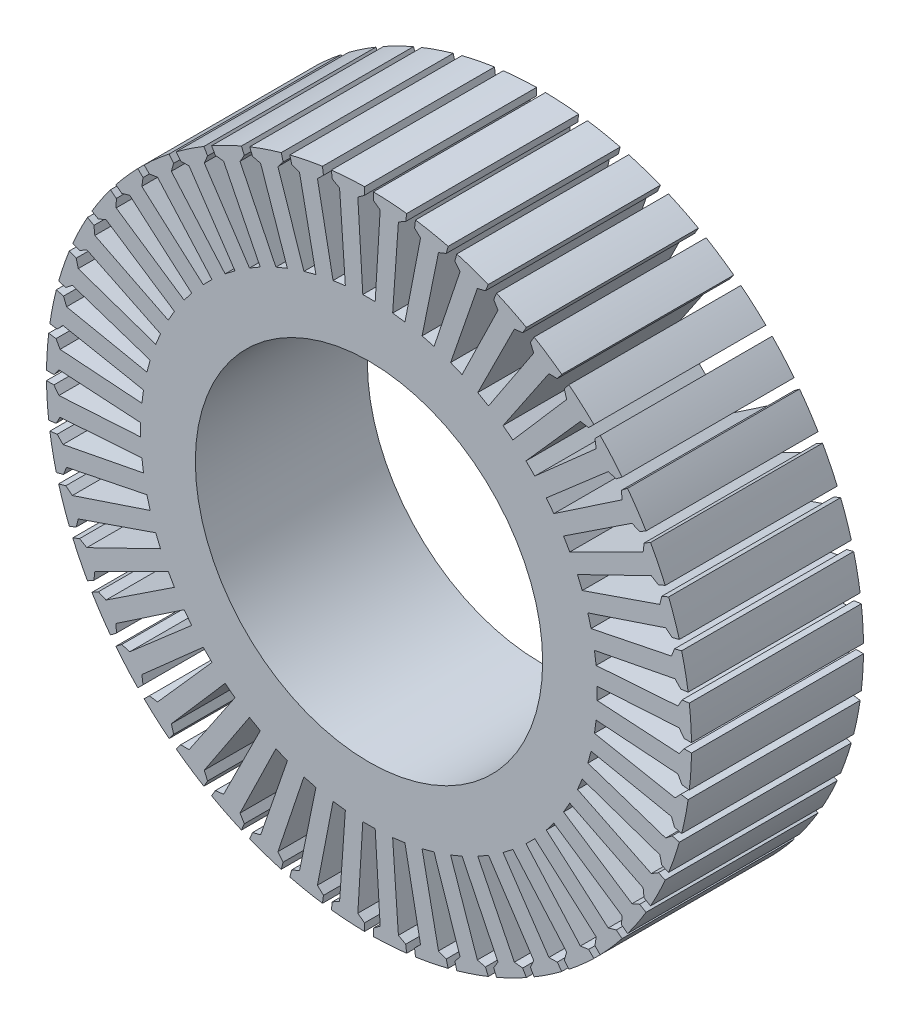
SolidWorks part; units mm, degrees
ref_plane "Спереди" through (0, 0, 0) normal (0, 0, 1) x (1, 0, 0)
ref_plane "Сверху" through (0, 0, 0) normal (0, 1, 0) x (1, 0, 0)
ref_plane "Справа" through (0, 0, 0) normal (1, 0, 0) x (0, 0, -1)
sketch "Эскиз1" plane through (0, 0, 0) normal (0, 0, 1) x (1, 0, 0)
  circle A0 centre (0, 0) radius 75
  circle A1 centre (0, 0) radius 40.3846
extrude "Stator_stack" add sketch "Эскиз1" along normal blind 40 from offset 20
sketch "Эскиз2" plane through (0, 0, 0) normal (0, 0, 1) x (1, 0, 0)
  line L0 (75.9929, -1.0385) -> (73.2692, -1.0385)
  line L1 (73.2692, -1.0385) -> (72.1154, -2.5962)
  line L2 (72.1154, -2.5962) -> (53.0769, -1.4423)
  line L3 (53.0769, -1.4423) -> (53.0769, 1.4423)
  line L4 (53.0769, 1.4423) -> (72.1154, 2.5962)
  line L5 (72.1154, 2.5962) -> (73.2692, 1.0385)
  line L6 (73.2692, 1.0385) -> (75.9929, 1.0385)
  line L7 (75.9929, 1.0385) -> (75.9929, -1.0385)
  line L8 (75.4783, 8.8895) -> (72.7779, 8.534)
  line L9 (72.7779, 8.534) -> (71.8373, 6.839)
  line L10 (71.8373, 6.839) -> (52.8111, 5.498)
  line L11 (52.8111, 5.498) -> (52.4346, 8.3579)
  line L12 (52.4346, 8.3579) -> (71.1596, 11.9869)
  line L13 (71.1596, 11.9869) -> (72.5069, 10.5931)
  line L14 (72.5069, 10.5931) -> (75.2072, 10.9486)
  line L15 (75.2072, 10.9486) -> (75.4783, 8.8895)
  line L16 (73.6723, 18.6653) -> (71.0414, 17.9604)
  line L17 (71.0414, 17.9604) -> (70.33, 16.1571)
  line L18 (70.33, 16.1571) -> (51.6417, 12.3442)
  line L19 (51.6417, 12.3442) -> (50.8951, 15.1305)
  line L20 (50.8951, 15.1305) -> (68.9862, 21.1725)
  line L21 (68.9862, 21.1725) -> (70.5039, 19.9665)
  line L22 (70.5039, 19.9665) -> (73.1347, 20.6715)
  line L23 (73.1347, 20.6715) -> (73.6723, 18.6653)
  line L24 (70.6057, 28.1218) -> (68.0893, 27.0795)
  line L25 (68.0893, 27.0795) -> (67.6194, 25.1988)
  line L26 (67.6194, 25.1988) -> (49.5886, 18.9791)
  line L27 (49.5886, 18.9791) -> (48.4847, 21.6442)
  line L28 (48.4847, 21.6442) -> (65.6324, 29.9959)
  line L29 (65.6324, 29.9959) -> (67.2945, 28.9983)
  line L30 (67.2945, 28.9983) -> (69.8109, 30.0406)
  line L31 (69.8109, 30.0406) -> (70.6057, 28.1218)
  line L32 (66.331, 37.0971) -> (63.9722, 35.7353)
  line L33 (63.9722, 35.7353) -> (63.7518, 33.8094)
  line L34 (63.7518, 33.8094) -> (46.6871, 25.2894)
  line L35 (46.6871, 25.2894) -> (45.2448, 27.7875)
  line L36 (45.2448, 27.7875) -> (61.1557, 38.306)
  line L37 (61.1557, 38.306) -> (62.9338, 37.5339)
  line L38 (62.9338, 37.5339) -> (65.2926, 38.8958)
  line L39 (65.2926, 38.8958) -> (66.331, 37.0971)
  line L40 (60.9214, 45.4377) -> (58.7606, 43.7796)
  line L41 (58.7606, 43.7796) -> (58.7934, 41.8414)
  line L42 (58.7934, 41.8414) -> (42.9868, 31.1669)
  line L43 (42.9868, 31.1669) -> (41.2307, 33.4554)
  line L44 (41.2307, 33.4554) -> (55.6325, 45.9607)
  line L45 (55.6325, 45.9607) -> (57.4962, 45.4273)
  line L46 (57.4962, 45.4273) -> (59.657, 47.0854)
  line L47 (59.657, 47.0854) -> (60.9214, 45.4377)
  line L48 (54.4694, 53.0008) -> (52.5435, 51.0749)
  line L49 (52.5435, 51.0749) -> (52.829, 49.1575)
  line L50 (52.829, 49.1575) -> (38.5509, 36.5112)
  line L51 (38.5509, 36.5112) -> (36.5112, 38.5509)
  line L52 (36.5112, 38.5509) -> (49.1575, 52.829)
  line L53 (49.1575, 52.829) -> (51.0749, 52.5435)
  line L54 (51.0749, 52.5435) -> (53.0008, 54.4694)
  line L55 (53.0008, 54.4694) -> (54.4694, 53.0008)
  line L56 (47.0854, 59.657) -> (45.4273, 57.4962)
  line L57 (45.4273, 57.4962) -> (45.9607, 55.6325)
  line L58 (45.9607, 55.6325) -> (33.4554, 41.2307)
  line L59 (33.4554, 41.2307) -> (31.1669, 42.9868)
  line L60 (31.1669, 42.9868) -> (41.8414, 58.7934)
  line L61 (41.8414, 58.7934) -> (43.7796, 58.7606)
  line L62 (43.7796, 58.7606) -> (45.4377, 60.9214)
  line L63 (45.4377, 60.9214) -> (47.0854, 59.657)
  line L64 (38.8958, 65.2926) -> (37.5339, 62.9338)
  line L65 (37.5339, 62.9338) -> (38.306, 61.1557)
  line L66 (38.306, 61.1557) -> (27.7875, 45.2448)
  line L67 (27.7875, 45.2448) -> (25.2894, 46.6871)
  line L68 (25.2894, 46.6871) -> (33.8094, 63.7518)
  line L69 (33.8094, 63.7518) -> (35.7353, 63.9722)
  line L70 (35.7353, 63.9722) -> (37.0971, 66.331)
  line L71 (37.0971, 66.331) -> (38.8958, 65.2926)
  line L72 (30.0406, 69.8109) -> (28.9983, 67.2945)
  line L73 (28.9983, 67.2945) -> (29.9959, 65.6324)
  line L74 (29.9959, 65.6324) -> (21.6442, 48.4847)
  line L75 (21.6442, 48.4847) -> (18.9791, 49.5886)
  line L76 (18.9791, 49.5886) -> (25.1988, 67.6194)
  line L77 (25.1988, 67.6194) -> (27.0795, 68.0893)
  line L78 (27.0795, 68.0893) -> (28.1218, 70.6057)
  line L79 (28.1218, 70.6057) -> (30.0406, 69.8109)
  line L80 (20.6715, 73.1347) -> (19.9665, 70.5039)
  line L81 (19.9665, 70.5039) -> (21.1725, 68.9862)
  line L82 (21.1725, 68.9862) -> (15.1305, 50.8951)
  line L83 (15.1305, 50.8951) -> (12.3442, 51.6417)
  line L84 (12.3442, 51.6417) -> (16.1571, 70.33)
  line L85 (16.1571, 70.33) -> (17.9604, 71.0414)
  line L86 (17.9604, 71.0414) -> (18.6653, 73.6723)
  line L87 (18.6653, 73.6723) -> (20.6715, 73.1347)
  line L88 (10.9486, 75.2072) -> (10.5931, 72.5069)
  line L89 (10.5931, 72.5069) -> (11.9869, 71.1596)
  line L90 (11.9869, 71.1596) -> (8.3579, 52.4346)
  line L91 (8.3579, 52.4346) -> (5.498, 52.8111)
  line L92 (5.498, 52.8111) -> (6.839, 71.8373)
  line L93 (6.839, 71.8373) -> (8.534, 72.7779)
  line L94 (8.534, 72.7779) -> (8.8895, 75.4783)
  line L95 (8.8895, 75.4783) -> (10.9486, 75.2072)
  line L96 (1.0385, 75.9929) -> (1.0385, 73.2692)
  line L97 (1.0385, 73.2692) -> (2.5962, 72.1154)
  line L98 (2.5962, 72.1154) -> (1.4423, 53.0769)
  line L99 (1.4423, 53.0769) -> (-1.4423, 53.0769)
  line L100 (-1.4423, 53.0769) -> (-2.5962, 72.1154)
  line L101 (-2.5962, 72.1154) -> (-1.0385, 73.2692)
  line L102 (-1.0385, 73.2692) -> (-1.0385, 75.9929)
  line L103 (-1.0385, 75.9929) -> (1.0385, 75.9929)
  line L104 (-8.8895, 75.4783) -> (-8.534, 72.7779)
  line L105 (-8.534, 72.7779) -> (-6.839, 71.8373)
  line L106 (-6.839, 71.8373) -> (-5.498, 52.8111)
  line L107 (-5.498, 52.8111) -> (-8.3579, 52.4346)
  line L108 (-8.3579, 52.4346) -> (-11.9869, 71.1596)
  line L109 (-11.9869, 71.1596) -> (-10.5931, 72.5069)
  line L110 (-10.5931, 72.5069) -> (-10.9486, 75.2072)
  line L111 (-10.9486, 75.2072) -> (-8.8895, 75.4783)
  line L112 (-18.6653, 73.6723) -> (-17.9604, 71.0414)
  line L113 (-17.9604, 71.0414) -> (-16.1571, 70.33)
  line L114 (-16.1571, 70.33) -> (-12.3442, 51.6417)
  line L115 (-12.3442, 51.6417) -> (-15.1305, 50.8951)
  line L116 (-15.1305, 50.8951) -> (-21.1725, 68.9862)
  line L117 (-21.1725, 68.9862) -> (-19.9665, 70.5039)
  line L118 (-19.9665, 70.5039) -> (-20.6715, 73.1347)
  line L119 (-20.6715, 73.1347) -> (-18.6653, 73.6723)
  line L120 (-28.1218, 70.6057) -> (-27.0795, 68.0893)
  line L121 (-27.0795, 68.0893) -> (-25.1988, 67.6194)
  line L122 (-25.1988, 67.6194) -> (-18.9791, 49.5886)
  line L123 (-18.9791, 49.5886) -> (-21.6442, 48.4847)
  line L124 (-21.6442, 48.4847) -> (-29.9959, 65.6324)
  line L125 (-29.9959, 65.6324) -> (-28.9983, 67.2945)
  line L126 (-28.9983, 67.2945) -> (-30.0406, 69.8109)
  line L127 (-30.0406, 69.8109) -> (-28.1218, 70.6057)
  line L128 (-37.0971, 66.331) -> (-35.7353, 63.9722)
  line L129 (-35.7353, 63.9722) -> (-33.8094, 63.7518)
  line L130 (-33.8094, 63.7518) -> (-25.2894, 46.6871)
  line L131 (-25.2894, 46.6871) -> (-27.7875, 45.2448)
  line L132 (-27.7875, 45.2448) -> (-38.306, 61.1557)
  line L133 (-38.306, 61.1557) -> (-37.5339, 62.9338)
  line L134 (-37.5339, 62.9338) -> (-38.8958, 65.2926)
  line L135 (-38.8958, 65.2926) -> (-37.0971, 66.331)
  line L136 (-45.4377, 60.9214) -> (-43.7796, 58.7606)
  line L137 (-43.7796, 58.7606) -> (-41.8414, 58.7934)
  line L138 (-41.8414, 58.7934) -> (-31.1669, 42.9868)
  line L139 (-31.1669, 42.9868) -> (-33.4554, 41.2307)
  line L140 (-33.4554, 41.2307) -> (-45.9607, 55.6325)
  line L141 (-45.9607, 55.6325) -> (-45.4273, 57.4962)
  line L142 (-45.4273, 57.4962) -> (-47.0854, 59.657)
  line L143 (-47.0854, 59.657) -> (-45.4377, 60.9214)
  line L144 (-53.0008, 54.4694) -> (-51.0749, 52.5435)
  line L145 (-51.0749, 52.5435) -> (-49.1575, 52.829)
  line L146 (-49.1575, 52.829) -> (-36.5112, 38.5509)
  line L147 (-36.5112, 38.5509) -> (-38.5509, 36.5112)
  line L148 (-38.5509, 36.5112) -> (-52.829, 49.1575)
  line L149 (-52.829, 49.1575) -> (-52.5435, 51.0749)
  line L150 (-52.5435, 51.0749) -> (-54.4694, 53.0008)
  line L151 (-54.4694, 53.0008) -> (-53.0008, 54.4694)
  line L152 (-59.657, 47.0854) -> (-57.4962, 45.4273)
  line L153 (-57.4962, 45.4273) -> (-55.6325, 45.9607)
  line L154 (-55.6325, 45.9607) -> (-41.2307, 33.4554)
  line L155 (-41.2307, 33.4554) -> (-42.9868, 31.1669)
  line L156 (-42.9868, 31.1669) -> (-58.7934, 41.8414)
  line L157 (-58.7934, 41.8414) -> (-58.7606, 43.7796)
  line L158 (-58.7606, 43.7796) -> (-60.9214, 45.4377)
  line L159 (-60.9214, 45.4377) -> (-59.657, 47.0854)
  line L160 (-65.2926, 38.8958) -> (-62.9338, 37.5339)
  line L161 (-62.9338, 37.5339) -> (-61.1557, 38.306)
  line L162 (-61.1557, 38.306) -> (-45.2448, 27.7875)
  line L163 (-45.2448, 27.7875) -> (-46.6871, 25.2894)
  line L164 (-46.6871, 25.2894) -> (-63.7518, 33.8094)
  line L165 (-63.7518, 33.8094) -> (-63.9722, 35.7353)
  line L166 (-63.9722, 35.7353) -> (-66.331, 37.0971)
  line L167 (-66.331, 37.0971) -> (-65.2926, 38.8958)
  line L168 (-69.8109, 30.0406) -> (-67.2945, 28.9983)
  line L169 (-67.2945, 28.9983) -> (-65.6324, 29.9959)
  line L170 (-65.6324, 29.9959) -> (-48.4847, 21.6442)
  line L171 (-48.4847, 21.6442) -> (-49.5886, 18.9791)
  line L172 (-49.5886, 18.9791) -> (-67.6194, 25.1988)
  line L173 (-67.6194, 25.1988) -> (-68.0893, 27.0795)
  line L174 (-68.0893, 27.0795) -> (-70.6057, 28.1218)
  line L175 (-70.6057, 28.1218) -> (-69.8109, 30.0406)
  line L176 (-73.1347, 20.6715) -> (-70.5039, 19.9665)
  line L177 (-70.5039, 19.9665) -> (-68.9862, 21.1725)
  line L178 (-68.9862, 21.1725) -> (-50.8951, 15.1305)
  line L179 (-50.8951, 15.1305) -> (-51.6417, 12.3442)
  line L180 (-51.6417, 12.3442) -> (-70.33, 16.1571)
  line L181 (-70.33, 16.1571) -> (-71.0414, 17.9604)
  line L182 (-71.0414, 17.9604) -> (-73.6723, 18.6653)
  line L183 (-73.6723, 18.6653) -> (-73.1347, 20.6715)
  line L184 (-75.2072, 10.9486) -> (-72.5069, 10.5931)
  line L185 (-72.5069, 10.5931) -> (-71.1596, 11.9869)
  line L186 (-71.1596, 11.9869) -> (-52.4346, 8.3579)
  line L187 (-52.4346, 8.3579) -> (-52.8111, 5.498)
  line L188 (-52.8111, 5.498) -> (-71.8373, 6.839)
  line L189 (-71.8373, 6.839) -> (-72.7779, 8.534)
  line L190 (-72.7779, 8.534) -> (-75.4783, 8.8895)
  line L191 (-75.4783, 8.8895) -> (-75.2072, 10.9486)
  line L192 (-75.9929, 1.0385) -> (-73.2692, 1.0385)
  line L193 (-73.2692, 1.0385) -> (-72.1154, 2.5962)
  line L194 (-72.1154, 2.5962) -> (-53.0769, 1.4423)
  line L195 (-53.0769, 1.4423) -> (-53.0769, -1.4423)
  line L196 (-53.0769, -1.4423) -> (-72.1154, -2.5962)
  line L197 (-72.1154, -2.5962) -> (-73.2692, -1.0385)
  line L198 (-73.2692, -1.0385) -> (-75.9929, -1.0385)
  line L199 (-75.9929, -1.0385) -> (-75.9929, 1.0385)
  line L200 (-75.4783, -8.8895) -> (-72.7779, -8.534)
  line L201 (-72.7779, -8.534) -> (-71.8373, -6.839)
  line L202 (-71.8373, -6.839) -> (-52.8111, -5.498)
  line L203 (-52.8111, -5.498) -> (-52.4346, -8.3579)
  line L204 (-52.4346, -8.3579) -> (-71.1596, -11.9869)
  line L205 (-71.1596, -11.9869) -> (-72.5069, -10.5931)
  line L206 (-72.5069, -10.5931) -> (-75.2072, -10.9486)
  line L207 (-75.2072, -10.9486) -> (-75.4783, -8.8895)
  line L208 (-73.6723, -18.6653) -> (-71.0414, -17.9604)
  line L209 (-71.0414, -17.9604) -> (-70.33, -16.1571)
  line L210 (-70.33, -16.1571) -> (-51.6417, -12.3442)
  line L211 (-51.6417, -12.3442) -> (-50.8951, -15.1305)
  line L212 (-50.8951, -15.1305) -> (-68.9862, -21.1725)
  line L213 (-68.9862, -21.1725) -> (-70.5039, -19.9665)
  line L214 (-70.5039, -19.9665) -> (-73.1347, -20.6715)
  line L215 (-73.1347, -20.6715) -> (-73.6723, -18.6653)
  line L216 (-70.6057, -28.1218) -> (-68.0893, -27.0795)
  line L217 (-68.0893, -27.0795) -> (-67.6194, -25.1988)
  line L218 (-67.6194, -25.1988) -> (-49.5886, -18.9791)
  line L219 (-49.5886, -18.9791) -> (-48.4847, -21.6442)
  line L220 (-48.4847, -21.6442) -> (-65.6324, -29.9959)
  line L221 (-65.6324, -29.9959) -> (-67.2945, -28.9983)
  line L222 (-67.2945, -28.9983) -> (-69.8109, -30.0406)
  line L223 (-69.8109, -30.0406) -> (-70.6057, -28.1218)
  line L224 (-66.331, -37.0971) -> (-63.9722, -35.7353)
  line L225 (-63.9722, -35.7353) -> (-63.7518, -33.8094)
  line L226 (-63.7518, -33.8094) -> (-46.6871, -25.2894)
  line L227 (-46.6871, -25.2894) -> (-45.2448, -27.7875)
  line L228 (-45.2448, -27.7875) -> (-61.1557, -38.306)
  line L229 (-61.1557, -38.306) -> (-62.9338, -37.5339)
  line L230 (-62.9338, -37.5339) -> (-65.2926, -38.8958)
  line L231 (-65.2926, -38.8958) -> (-66.331, -37.0971)
  line L232 (-60.9214, -45.4377) -> (-58.7606, -43.7796)
  line L233 (-58.7606, -43.7796) -> (-58.7934, -41.8414)
  line L234 (-58.7934, -41.8414) -> (-42.9868, -31.1669)
  line L235 (-42.9868, -31.1669) -> (-41.2307, -33.4554)
  line L236 (-41.2307, -33.4554) -> (-55.6325, -45.9607)
  line L237 (-55.6325, -45.9607) -> (-57.4962, -45.4273)
  line L238 (-57.4962, -45.4273) -> (-59.657, -47.0854)
  line L239 (-59.657, -47.0854) -> (-60.9214, -45.4377)
  line L240 (-54.4694, -53.0008) -> (-52.5435, -51.0749)
  line L241 (-52.5435, -51.0749) -> (-52.829, -49.1575)
  line L242 (-52.829, -49.1575) -> (-38.5509, -36.5112)
  line L243 (-38.5509, -36.5112) -> (-36.5112, -38.5509)
  line L244 (-36.5112, -38.5509) -> (-49.1575, -52.829)
  line L245 (-49.1575, -52.829) -> (-51.0749, -52.5435)
  line L246 (-51.0749, -52.5435) -> (-53.0008, -54.4694)
  line L247 (-53.0008, -54.4694) -> (-54.4694, -53.0008)
  line L248 (-47.0854, -59.657) -> (-45.4273, -57.4962)
  line L249 (-45.4273, -57.4962) -> (-45.9607, -55.6325)
  line L250 (-45.9607, -55.6325) -> (-33.4554, -41.2307)
  line L251 (-33.4554, -41.2307) -> (-31.1669, -42.9868)
  line L252 (-31.1669, -42.9868) -> (-41.8414, -58.7934)
  line L253 (-41.8414, -58.7934) -> (-43.7796, -58.7606)
  line L254 (-43.7796, -58.7606) -> (-45.4377, -60.9214)
  line L255 (-45.4377, -60.9214) -> (-47.0854, -59.657)
  line L256 (-38.8958, -65.2926) -> (-37.5339, -62.9338)
  line L257 (-37.5339, -62.9338) -> (-38.306, -61.1557)
  line L258 (-38.306, -61.1557) -> (-27.7875, -45.2448)
  line L259 (-27.7875, -45.2448) -> (-25.2894, -46.6871)
  line L260 (-25.2894, -46.6871) -> (-33.8094, -63.7518)
  line L261 (-33.8094, -63.7518) -> (-35.7353, -63.9722)
  line L262 (-35.7353, -63.9722) -> (-37.0971, -66.331)
  line L263 (-37.0971, -66.331) -> (-38.8958, -65.2926)
  line L264 (-30.0406, -69.8109) -> (-28.9983, -67.2945)
  line L265 (-28.9983, -67.2945) -> (-29.9959, -65.6324)
  line L266 (-29.9959, -65.6324) -> (-21.6442, -48.4847)
  line L267 (-21.6442, -48.4847) -> (-18.9791, -49.5886)
  line L268 (-18.9791, -49.5886) -> (-25.1988, -67.6194)
  line L269 (-25.1988, -67.6194) -> (-27.0795, -68.0893)
  line L270 (-27.0795, -68.0893) -> (-28.1218, -70.6057)
  line L271 (-28.1218, -70.6057) -> (-30.0406, -69.8109)
  line L272 (-20.6715, -73.1347) -> (-19.9665, -70.5039)
  line L273 (-19.9665, -70.5039) -> (-21.1725, -68.9862)
  line L274 (-21.1725, -68.9862) -> (-15.1305, -50.8951)
  line L275 (-15.1305, -50.8951) -> (-12.3442, -51.6417)
  line L276 (-12.3442, -51.6417) -> (-16.1571, -70.33)
  line L277 (-16.1571, -70.33) -> (-17.9604, -71.0414)
  line L278 (-17.9604, -71.0414) -> (-18.6653, -73.6723)
  line L279 (-18.6653, -73.6723) -> (-20.6715, -73.1347)
  line L280 (-10.9486, -75.2072) -> (-10.5931, -72.5069)
  line L281 (-10.5931, -72.5069) -> (-11.9869, -71.1596)
  line L282 (-11.9869, -71.1596) -> (-8.3579, -52.4346)
  line L283 (-8.3579, -52.4346) -> (-5.498, -52.8111)
  line L284 (-5.498, -52.8111) -> (-6.839, -71.8373)
  line L285 (-6.839, -71.8373) -> (-8.534, -72.7779)
  line L286 (-8.534, -72.7779) -> (-8.8895, -75.4783)
  line L287 (-8.8895, -75.4783) -> (-10.9486, -75.2072)
  line L288 (-1.0385, -75.9929) -> (-1.0385, -73.2692)
  line L289 (-1.0385, -73.2692) -> (-2.5962, -72.1154)
  line L290 (-2.5962, -72.1154) -> (-1.4423, -53.0769)
  line L291 (-1.4423, -53.0769) -> (1.4423, -53.0769)
  line L292 (1.4423, -53.0769) -> (2.5962, -72.1154)
  line L293 (2.5962, -72.1154) -> (1.0385, -73.2692)
  line L294 (1.0385, -73.2692) -> (1.0385, -75.9929)
  line L295 (1.0385, -75.9929) -> (-1.0385, -75.9929)
  line L296 (8.8895, -75.4783) -> (8.534, -72.7779)
  line L297 (8.534, -72.7779) -> (6.839, -71.8373)
  line L298 (6.839, -71.8373) -> (5.498, -52.8111)
  line L299 (5.498, -52.8111) -> (8.3579, -52.4346)
  line L300 (8.3579, -52.4346) -> (11.9869, -71.1596)
  line L301 (11.9869, -71.1596) -> (10.5931, -72.5069)
  line L302 (10.5931, -72.5069) -> (10.9486, -75.2072)
  line L303 (10.9486, -75.2072) -> (8.8895, -75.4783)
  line L304 (18.6653, -73.6723) -> (17.9604, -71.0414)
  line L305 (17.9604, -71.0414) -> (16.1571, -70.33)
  line L306 (16.1571, -70.33) -> (12.3442, -51.6417)
  line L307 (12.3442, -51.6417) -> (15.1305, -50.8951)
  line L308 (15.1305, -50.8951) -> (21.1725, -68.9862)
  line L309 (21.1725, -68.9862) -> (19.9665, -70.5039)
  line L310 (19.9665, -70.5039) -> (20.6715, -73.1347)
  line L311 (20.6715, -73.1347) -> (18.6653, -73.6723)
  line L312 (28.1218, -70.6057) -> (27.0795, -68.0893)
  line L313 (27.0795, -68.0893) -> (25.1988, -67.6194)
  line L314 (25.1988, -67.6194) -> (18.9791, -49.5886)
  line L315 (18.9791, -49.5886) -> (21.6442, -48.4847)
  line L316 (21.6442, -48.4847) -> (29.9959, -65.6324)
  line L317 (29.9959, -65.6324) -> (28.9983, -67.2945)
  line L318 (28.9983, -67.2945) -> (30.0406, -69.8109)
  line L319 (30.0406, -69.8109) -> (28.1218, -70.6057)
  line L320 (37.0971, -66.331) -> (35.7353, -63.9722)
  line L321 (35.7353, -63.9722) -> (33.8094, -63.7518)
  line L322 (33.8094, -63.7518) -> (25.2894, -46.6871)
  line L323 (25.2894, -46.6871) -> (27.7875, -45.2448)
  line L324 (27.7875, -45.2448) -> (38.306, -61.1557)
  line L325 (38.306, -61.1557) -> (37.5339, -62.9338)
  line L326 (37.5339, -62.9338) -> (38.8958, -65.2926)
  line L327 (38.8958, -65.2926) -> (37.0971, -66.331)
  line L328 (45.4377, -60.9214) -> (43.7796, -58.7606)
  line L329 (43.7796, -58.7606) -> (41.8414, -58.7934)
  line L330 (41.8414, -58.7934) -> (31.1669, -42.9868)
  line L331 (31.1669, -42.9868) -> (33.4554, -41.2307)
  line L332 (33.4554, -41.2307) -> (45.9607, -55.6325)
  line L333 (45.9607, -55.6325) -> (45.4273, -57.4962)
  line L334 (45.4273, -57.4962) -> (47.0854, -59.657)
  line L335 (47.0854, -59.657) -> (45.4377, -60.9214)
  line L336 (53.0008, -54.4694) -> (51.0749, -52.5435)
  line L337 (51.0749, -52.5435) -> (49.1575, -52.829)
  line L338 (49.1575, -52.829) -> (36.5112, -38.5509)
  line L339 (36.5112, -38.5509) -> (38.5509, -36.5112)
  line L340 (38.5509, -36.5112) -> (52.829, -49.1575)
  line L341 (52.829, -49.1575) -> (52.5435, -51.0749)
  line L342 (52.5435, -51.0749) -> (54.4694, -53.0008)
  line L343 (54.4694, -53.0008) -> (53.0008, -54.4694)
  line L344 (59.657, -47.0854) -> (57.4962, -45.4273)
  line L345 (57.4962, -45.4273) -> (55.6325, -45.9607)
  line L346 (55.6325, -45.9607) -> (41.2307, -33.4554)
  line L347 (41.2307, -33.4554) -> (42.9868, -31.1669)
  line L348 (42.9868, -31.1669) -> (58.7934, -41.8414)
  line L349 (58.7934, -41.8414) -> (58.7606, -43.7796)
  line L350 (58.7606, -43.7796) -> (60.9214, -45.4377)
  line L351 (60.9214, -45.4377) -> (59.657, -47.0854)
  line L352 (65.2926, -38.8958) -> (62.9338, -37.5339)
  line L353 (62.9338, -37.5339) -> (61.1557, -38.306)
  line L354 (61.1557, -38.306) -> (45.2448, -27.7875)
  line L355 (45.2448, -27.7875) -> (46.6871, -25.2894)
  line L356 (46.6871, -25.2894) -> (63.7518, -33.8094)
  line L357 (63.7518, -33.8094) -> (63.9722, -35.7353)
  line L358 (63.9722, -35.7353) -> (66.331, -37.0971)
  line L359 (66.331, -37.0971) -> (65.2926, -38.8958)
  line L360 (69.8109, -30.0406) -> (67.2945, -28.9983)
  line L361 (67.2945, -28.9983) -> (65.6324, -29.9959)
  line L362 (65.6324, -29.9959) -> (48.4847, -21.6442)
  line L363 (48.4847, -21.6442) -> (49.5886, -18.9791)
  line L364 (49.5886, -18.9791) -> (67.6194, -25.1988)
  line L365 (67.6194, -25.1988) -> (68.0893, -27.0795)
  line L366 (68.0893, -27.0795) -> (70.6057, -28.1218)
  line L367 (70.6057, -28.1218) -> (69.8109, -30.0406)
  line L368 (73.1347, -20.6715) -> (70.5039, -19.9665)
  line L369 (70.5039, -19.9665) -> (68.9862, -21.1725)
  line L370 (68.9862, -21.1725) -> (50.8951, -15.1305)
  line L371 (50.8951, -15.1305) -> (51.6417, -12.3442)
  line L372 (51.6417, -12.3442) -> (70.33, -16.1571)
  line L373 (70.33, -16.1571) -> (71.0414, -17.9604)
  line L374 (71.0414, -17.9604) -> (73.6723, -18.6653)
  line L375 (73.6723, -18.6653) -> (73.1347, -20.6715)
  line L376 (75.2072, -10.9486) -> (72.5069, -10.5931)
  line L377 (72.5069, -10.5931) -> (71.1596, -11.9869)
  line L378 (71.1596, -11.9869) -> (52.4346, -8.3579)
  line L379 (52.4346, -8.3579) -> (52.8111, -5.498)
  line L380 (52.8111, -5.498) -> (71.8373, -6.839)
  line L381 (71.8373, -6.839) -> (72.7779, -8.534)
  line L382 (72.7779, -8.534) -> (75.4783, -8.8895)
  line L383 (75.4783, -8.8895) -> (75.2072, -10.9486)
extrude "Stator_48_slots" cut sketch "Эскиз2" against normal mid plane 42
